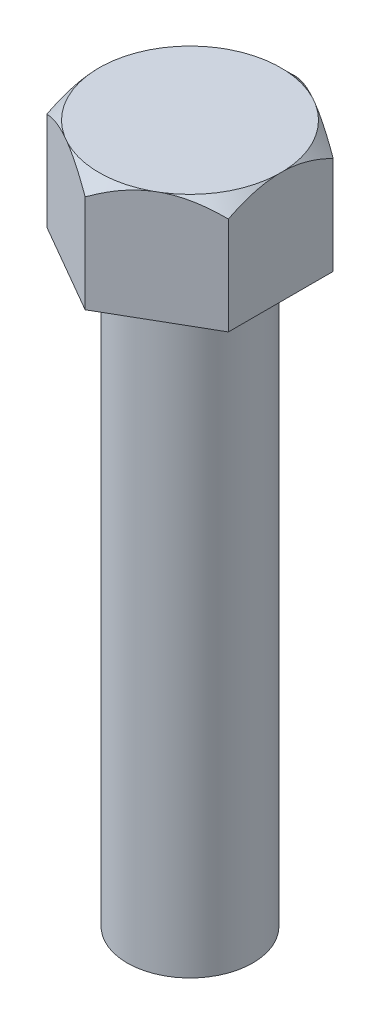
SolidWorks part; units mm, degrees
ref_plane "Front Plane" through (0, 0, 0) normal (0, 0, 1) x (1, 0, 0)
ref_plane "Top Plane" through (0, 0, 0) normal (0, 1, 0) x (1, 0, 0)
ref_plane "Right Plane" through (0, 0, 0) normal (1, 0, 0) x (0, 0, -1)
sketch "Sketch2" plane through (0, 0, 0) normal (0, 1, 0) x (1, 0, 0)
  circle A0 centre (0, 0) radius 2.25
  dimension "D1" = 4.5
extrude "Boss-Extrude1" add sketch "Sketch2" against normal blind 25
sketch "Sketch3" plane through (0, 0, 0) normal (0, 1, 0) x (1, 0, 0)
  line L1 (0, 3.7528) -> (-3.25, 1.8764)
  line L2 (-3.25, 1.8764) -> (-3.25, -1.8764)
  line L3 (-3.25, -1.8764) -> (0, -3.7528)
  line L4 (0, -3.7528) -> (3.25, -1.8764)
  line L5 (3.25, -1.8764) -> (3.25, 1.8764)
  line L6 (3.25, 1.8764) -> (0, 3.7528)
  circle A0 centre (0, 0) radius 3.25 construction
  dimension "D1" = 6.5
extrude "Boss-Extrude3" add sketch "Sketch3" against normal blind 4
sketch "Sketch5" plane through (0, 0, 0) normal (1, 0, 0) x (0, 0, -1)
  line L0 (3.2528, 0) -> (3.7528, 0)
  line L1 (3.7528, 0) -> (3.7528, -0.5)
  line L2 (3.7528, -0.5) -> (3.2528, 0)
  line L3 (0, 0) -> (0, -10.6582) construction
  dimension "D1" = 0.5
  dimension "D2" = 0.5
revolve "Cut-Revolve2" cut sketch "Sketch5" angle 360 about L3
